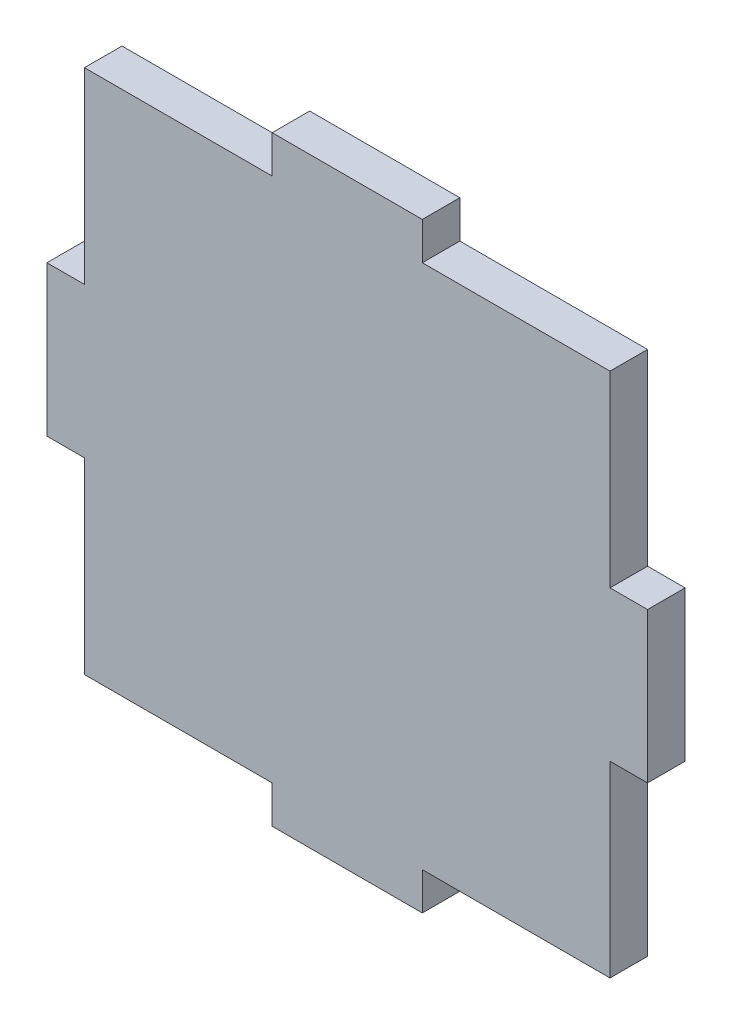
SolidWorks part; units mm, degrees
ref_plane "Front Plane" through (0, 0, 0) normal (0, 0, 1) x (1, 0, 0)
ref_plane "Top Plane" through (0, 0, 0) normal (0, 1, 0) x (1, 0, 0)
ref_plane "Right Plane" through (0, 0, 0) normal (1, 0, 0) x (0, 0, -1)
sketch "Sketch5" plane through (0, 0, 0) normal (0, 0, 1) x (1, 0, 0)
  line L0 (189.7628, -302.6284) -> (189.7628, -391.5284) construction
  line L1 (145.3128, -302.6284) -> (234.2128, -302.6284)
  line L2 (145.3128, -302.6284) -> (145.3128, -391.5284)
  line L3 (145.3128, -391.5284) -> (234.2128, -391.5284)
  line L4 (234.2128, -302.6284) -> (234.2128, -391.5284)
  line L5 (177.0628, -302.6284) -> (202.4628, -302.6284)
  line L6 (177.0628, -302.6284) -> (177.0628, -296.2784)
  line L7 (177.0628, -296.2784) -> (202.4628, -296.2784)
  line L8 (202.4628, -302.6284) -> (202.4628, -296.2784)
  line L9 (138.9628, -334.3784) -> (145.3128, -334.3784)
  line L10 (138.9628, -334.3784) -> (138.9628, -359.7784)
  line L11 (138.9628, -359.7784) -> (145.3128, -359.7784)
  line L12 (145.3128, -334.3784) -> (145.3128, -359.7784)
  line L13 (145.3128, -347.0784) -> (234.2128, -347.0784) construction
  line L14 (177.0628, -302.6284) -> (177.0628, -296.2784)
  line L15 (202.4628, -296.2784) -> (177.0628, -296.2784)
  line L16 (202.4628, -302.6284) -> (202.4628, -296.2784)
  line L17 (202.4628, -391.5284) -> (202.4628, -397.8784)
  line L18 (202.4628, -397.8784) -> (177.0628, -397.8784)
  line L19 (177.0628, -391.5284) -> (177.0628, -397.8784)
  line L20 (202.4628, -391.5284) -> (202.4628, -397.8784)
  line L21 (177.0628, -397.8784) -> (202.4628, -397.8784)
  line L22 (177.0628, -391.5284) -> (177.0628, -397.8784)
  line L23 (138.9628, -334.3784) -> (145.3128, -334.3784)
  line L24 (138.9628, -359.7784) -> (138.9628, -334.3784)
  line L25 (138.9628, -359.7784) -> (145.3128, -359.7784)
  line L26 (240.5628, -359.7784) -> (234.2128, -359.7784)
  line L27 (240.5628, -359.7784) -> (240.5628, -334.3784)
  line L28 (240.5628, -334.3784) -> (234.2128, -334.3784)
  line L29 (240.5628, -359.7784) -> (234.2128, -359.7784)
  line L30 (240.5628, -334.3784) -> (240.5628, -359.7784)
  line L31 (240.5628, -334.3784) -> (234.2128, -334.3784)
  dimension "D1" = 88.9
  dimension "D2" = 88.9
  dimension "D3" = 25.4
  dimension "D4" = 6.35
  dimension "D5" = 31.75
  dimension "D6" = 31.75
extrude "Boss-Extrude1" add sketch "Sketch5" along normal blind 6.35 contours L24 L25 L2 L23 | L3 L22 L21 L20 | L3 L19 L18 L17 | L27 L28 L4 L26 | L1 L16 L15 L14 | L30 L31 L4 L29 | L1 L8 L7 L6 | L10 L11 L2 L9
equation "\"width\"= 3.5in"
equation "\"Height\"= 18in"
equation "\"thick\"= 0.25"
equation "\"D1@Sketch5\"=\"width\""
equation "\"D2@Sketch5\"=\"width\""
equation "\"D4@Sketch5\"=\"thick\""
equation "\"D1@Boss-Extrude1\"=\"thick\""
